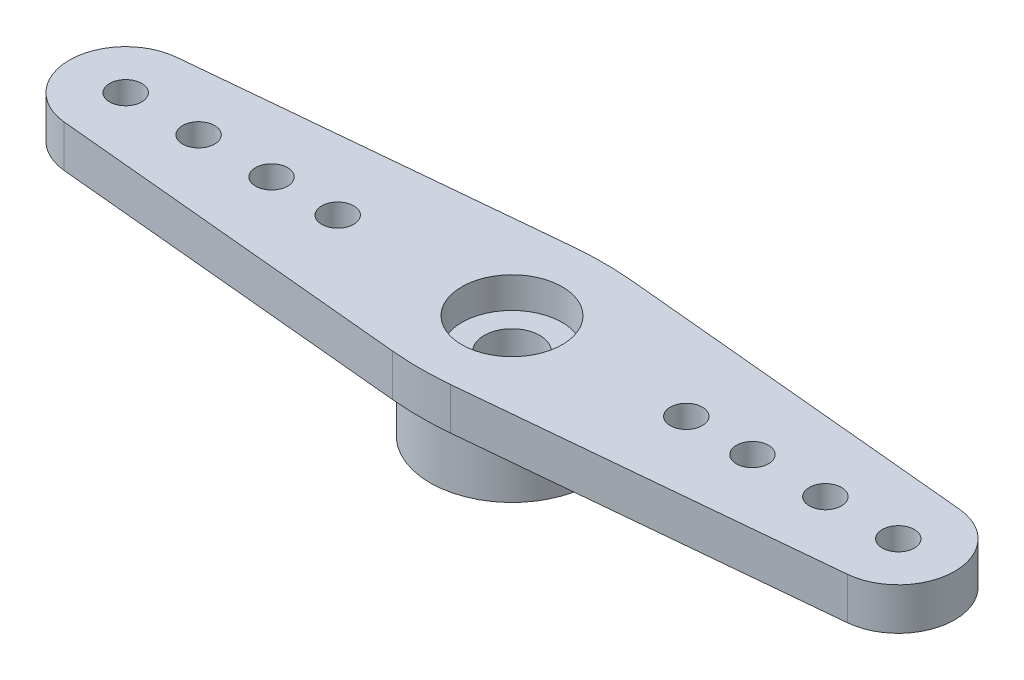
SolidWorks part; units mm, degrees
ref_plane "Front Plane" through (0, 0, 0) normal (0, 0, 1) x (1, 0, 0)
ref_plane "Top Plane" through (0, 0, 0) normal (0, 1, 0) x (1, 0, 0)
ref_plane "Right Plane" through (0, 0, 0) normal (1, 0, 0) x (0, 0, -1)
sketch "Sketch1" plane through (0, 0, 0) normal (0, 1, 0) x (1, 0, 0)
  circle A0 centre (0, 0) radius 3.3655
  circle A1 centre (0, 0) radius 2.2352
  dimension "D1" = 6.731
  dimension "D2" = 4.4704
extrude "Boss-Extrude1" add sketch "Sketch1" along normal blind 2.54
sketch "Sketch2" plane through (0, 2.54, 0) normal (0, 1, 0) x (1, 0, 0)
  line L0 (0, 0) -> (50000, 0) construction
  line L1 (0, 0) -> (0, 50000) construction
  line L2 (0, 3.8227) -> (16.0923, 2.3075)
  line L3 (0, -3.8227) -> (16.0923, -2.3075)
  line L4 (0, -3.8227) -> (-16.0923, -2.3075)
  line L5 (0, 3.8227) -> (-16.0923, 2.3075)
  circle A0 centre (15.875, 0) radius 0.6604
  circle A1 centre (12.8778, 0) radius 0.6604
  circle A2 centre (9.8806, 0) radius 0.6604
  circle A3 centre (7.1628, 0) radius 0.6604
  circle A4 centre (15.875, 0) radius 2.3178
  circle A5 centre (0, 0) radius 3.8227
  circle A6 centre (-15.875, 0) radius 2.3178
  circle A7 centre (-7.1628, 0) radius 0.6604
  circle A8 centre (-9.8806, 0) radius 0.6604
  circle A9 centre (-12.8778, 0) radius 0.6604
  circle A10 centre (-15.875, 0) radius 0.6604
  circle A11 centre (0, 0) radius 1.143
  circle M1 centre (0, 0) radius 3.3655
  circle M2 centre (0, 0) radius 2.2352
  dimension "D1" = 1.3208
  dimension "D6" = 4.6355
  dimension "D7" = 7.6454
  dimension "D8" = 2.286
  dimension "D2" = 15.875
  dimension "D3" = 2.9972
  dimension "D4" = 5.9944
  dimension "D5" = 8.7122
extrude "Boss-Extrude2" add sketch "Sketch2" along normal blind 1.7272 contours L5 A6 L4 A5 A8 A7 A9 | A6 A10 | A5 L3 A4 L2 A1 A2 A3 | A4 A0 | M1 M2 | L3 A5 L2 L5 L4 M1 | A11 M2
fillet "Fillet1" radius 12.7 2 edges at (0, 3.4036, -3.8227) (0, 3.4036, 3.8227)
sketch "Sketch3" plane through (0, 4.2672, 0) normal (0, 1, 0) x (1, 0, 0)
  circle A0 centre (0, 0) radius 2.0638
  circle M17 centre (0, 0) radius 1.143
  dimension "D1" = 4.1275
extrude "Cut-Extrude1" cut sketch "Sketch3" against normal blind 1.27 contours A0 M17
sketch "Esboço1" plane through (0, 2.54, 0) normal (0, -1, 0) x (1, 0, 0)
  circle A0 centre (0, 0) radius 1.143 construction
  circle A1 centre (0, 0) radius 2.2352
  circle A2 centre (0, 0) radius 2.2352
  circle A3 centre (0, 0) radius 1.143
  dimension "D1" = 0
extrude "Ressalto-extrusão1" add sketch "Esboço1" along normal blind 3.27
